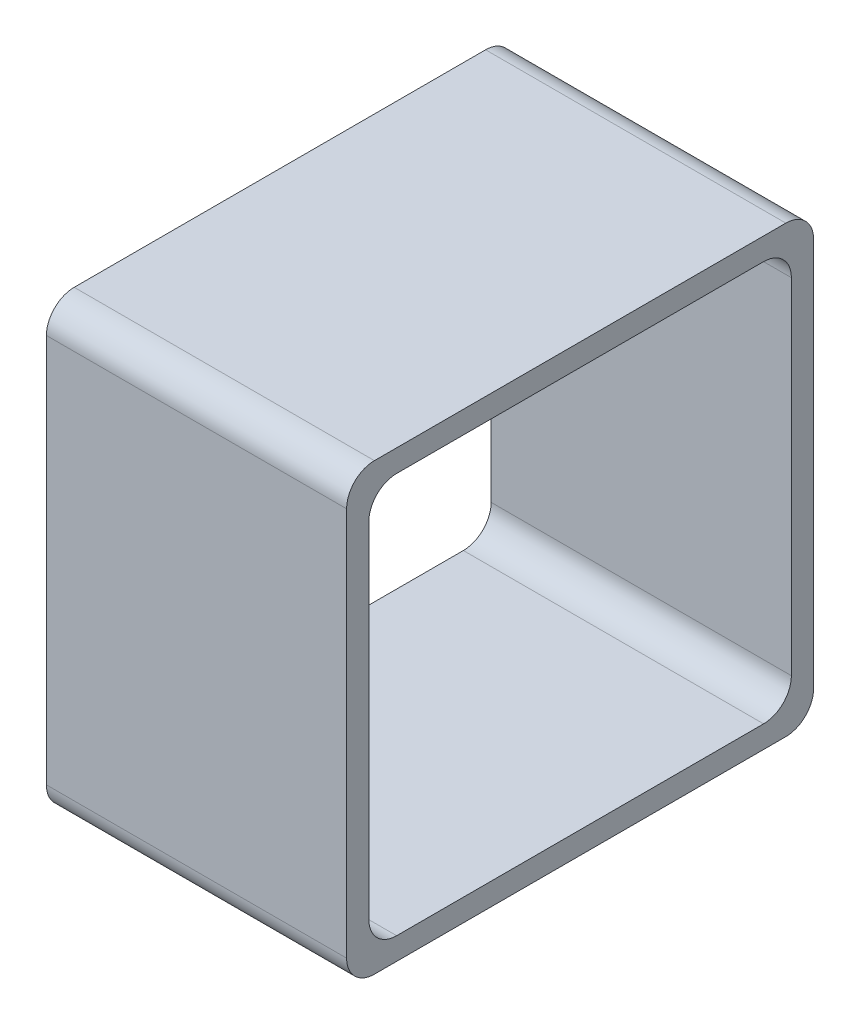
SolidWorks part; units mm, degrees
ref_plane "前视基准面" through (0, 0, 0) normal (0, 0, 1) x (1, 0, 0)
ref_plane "上视基准面" through (0, 0, 0) normal (0, 1, 0) x (1, 0, 0)
ref_plane "右视基准面" through (0, 0, 0) normal (1, 0, 0) x (0, 0, -1)
other "Configuration Table"
sketch "草图1" plane through (0, 0, 0) normal (1, 0, 0) x (0, 0, -1)
  line L0 (-21, -20) -> (21, -20)
  line L1 (-19, -18) -> (19, -18)
  line L2 (-19, -18) -> (-19, 18)
  line L3 (-19, 18) -> (19, 18)
  line L4 (19, -18) -> (19, 18)
  line L5 (-19, -18) -> (19, 18) construction
  line L6 (-19, 18) -> (19, -18) construction
  line L7 (21, -20) -> (21, 20)
  line L8 (-21, 20) -> (21, 20)
  line L9 (-21, -20) -> (-21, 20)
  point P0 (0, 0)
  dimension "D2" = 40
  dimension "D3" = 42
  dimension "D1" = 2
extrude "凸台-拉伸1" add sketch "草图1" along normal blind 27
fillet "圆角1" radius 2.5 8 edges at (13.5, 20, 21) (13.5, 18, 19) (13.5, -18, 19) (13.5, -20, 21) (13.5, 18, -19) (13.5, -18, -19) (13.5, -20, -21) (13.5, 20, -21)
